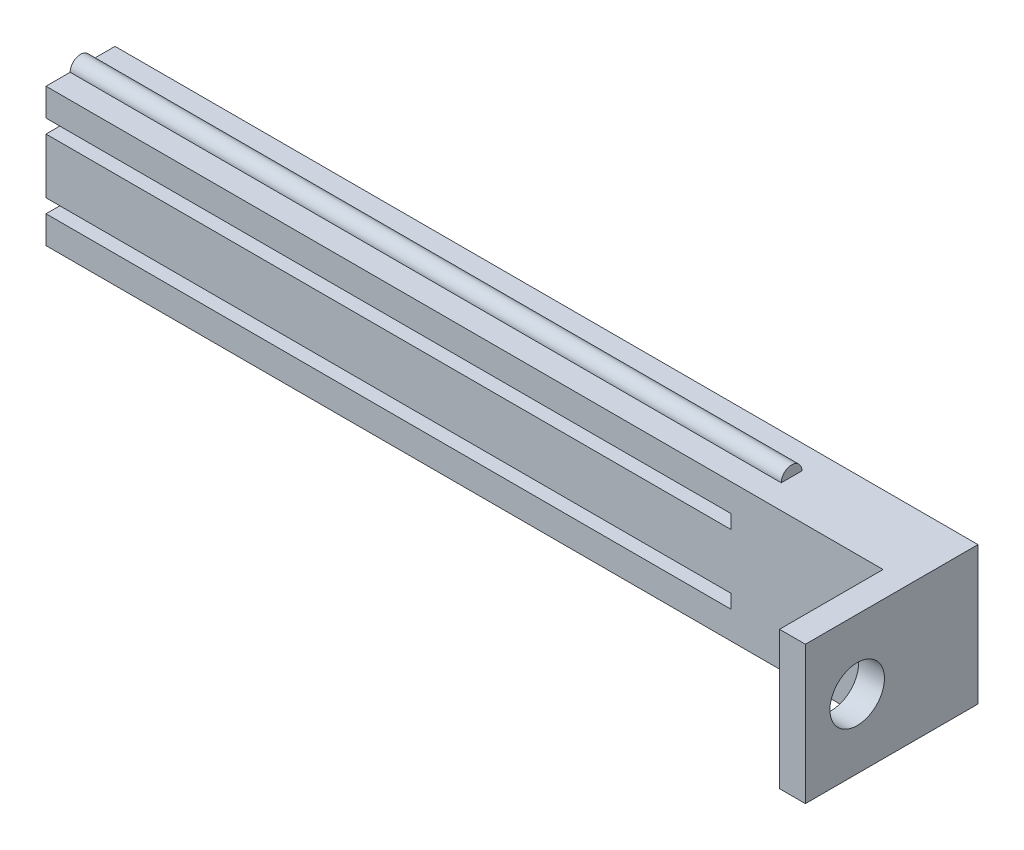
SolidWorks part; units mm, degrees
ref_plane "Front Plane" through (0, 0, 0) normal (0, 0, 1) x (1, 0, 0)
ref_plane "Top Plane" through (0, 0, 0) normal (0, 1, 0) x (1, 0, 0)
ref_plane "Right Plane" through (0, 0, 0) normal (1, 0, 0) x (0, 0, -1)
sketch "Sketch1" plane through (0, 0, 0) normal (0, 0, 1) x (1, 0, 0)
  line L1 (-147.2787, 68.6667) -> (102.7213, 68.6667)
  line L2 (-147.2787, 68.6667) -> (-147.2787, 28.6667)
  line L3 (-147.2787, 28.6667) -> (102.7213, 28.6667)
  line L4 (102.7213, 68.6667) -> (102.7213, 28.6667)
  dimension "D1" = 250
  dimension "D2" = 40
extrude "Boss-Extrude1" add sketch "Sketch1" along normal blind 20
sketch "Sketch2" plane through (0, 0, 20) normal (0, 0, 1) x (1, 0, 0)
  line L0 (-147.2787, 28.6667) -> (102.7213, 28.6667) construction
  line L1 (102.7213, 68.6667) -> (95.2213, 68.6667)
  line L2 (102.7213, 68.6667) -> (102.7213, 28.6667)
  line L3 (102.7213, 28.6667) -> (95.2213, 28.6667)
  line L4 (95.2213, 68.6667) -> (95.2213, 28.6667)
  dimension "D1" = 7.5
extrude "Boss-Extrude2" add sketch "Sketch2" along normal blind 30
sketch "Sketch4" plane through (-147.2787, 0, 0) normal (-1, 0, 0) x (0, 0, 1)
  line L0 (7, 68.6667) -> (13, 68.6667)
  line L1 (7, 28.6667) -> (13, 28.6667)
  arc A0 (13, 68.6667) -> (7, 68.6667) centre (10, 68.6667) ccw
  arc A1 (7, 28.6667) -> (13, 28.6667) centre (10, 28.6667) ccw
  dimension "D1" = 6
  dimension "D2" = 6
extrude "Boss-Extrude3" add sketch "Sketch4" against normal blind 206
sketch "Sketch6" plane through (-147.2787, 0, 0) normal (-1, 0, 0) x (0, 0, 1)
  line L0 (20, 68.6667) -> (20, 28.6667) construction
  line L1 (20, 60.6667) -> (15, 60.6667)
  line L2 (20, 60.6667) -> (20, 56.6667)
  line L3 (20, 56.6667) -> (15, 56.6667)
  line L6 (20, 68.6667) -> (13, 68.6667) construction
  line L7 (20, 40.6667) -> (15, 40.6667)
  line L8 (20, 40.6667) -> (20, 36.6667)
  line L9 (20, 36.6667) -> (15, 36.6667)
  line L11 (20, 28.6667) -> (13, 28.6667) construction
  line L12 (10, 63.6667) -> (10, 53.6667)
  line L13 (15, 56.6667) -> (15, 53.6667)
  line L14 (10, 63.6667) -> (15, 63.6667)
  line L15 (10, 63.6667) -> (10, 53.6667)
  line L16 (10, 53.6667) -> (15, 53.6667)
  line L17 (15, 63.6667) -> (15, 60.6667)
  line L18 (10, 43.6667) -> (15, 43.6667)
  line L19 (10, 43.6667) -> (10, 33.6667)
  line L20 (10, 33.6667) -> (15, 33.6667)
  line L21 (15, 43.6667) -> (15, 40.6667)
  line L22 (10, 43.6667) -> (10, 33.6667)
  line L24 (15, 36.6667) -> (15, 33.6667)
  point P27 (12.5, 63.6667)
  point P28 (12.5, 53.6667)
  line M24 (20, 28.6667) -> (20, 68.6667)
  dimension "D1" = 8
  dimension "D2" = 8
  dimension "D3" = 4
  dimension "D4" = 4
  dimension "D5" = 5
  dimension "D6" = 5
  dimension "D7" = 10
  dimension "D8" = 10
  dimension "D9" = 3
  dimension "D10" = 3
extrude "Cut-Extrude1" cut sketch "Sketch6" against normal blind 198.5 contours L17 L14 L12 L16 L13 L3 L1 M24 | L24 L9 L7 L21 L18 L19 L20 M24
sketch "Sketch7" plane through (95.2213, 0, 0) normal (-1, 0, 0) x (0, 0, 1)
  circle A0 centre (35, 48.6667) radius 7.9
  point P6 (35, 48.6667)
  dimension "D1" = 15.8
extrude "Cut-Extrude2" cut sketch "Sketch7" against normal through all
